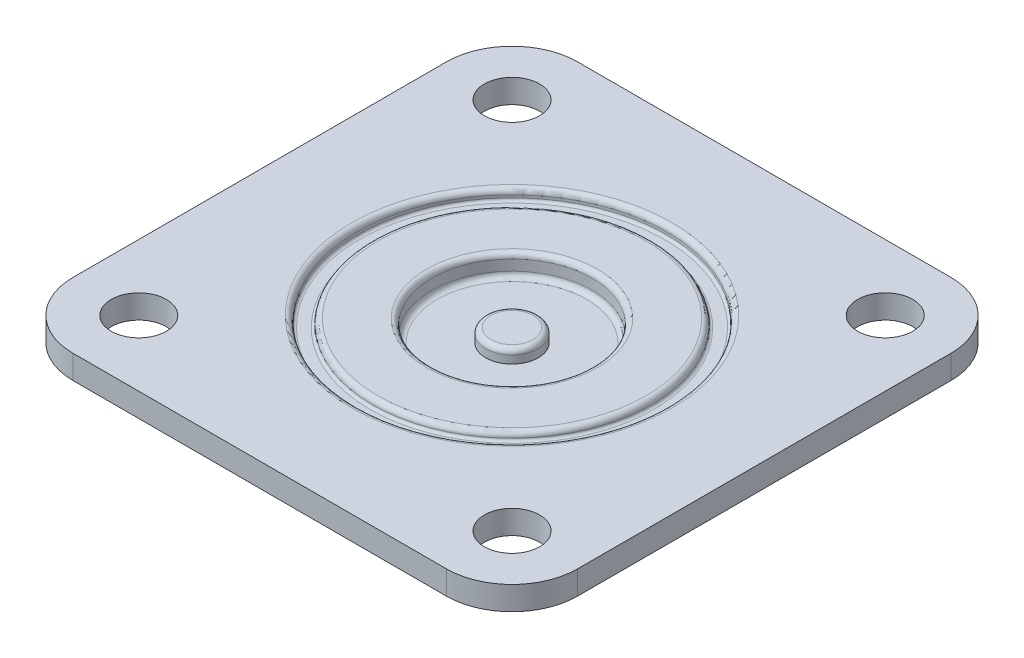
SolidWorks part; units mm, degrees
ref_plane "前视基准面" through (0, 0, 0) normal (0, 0, 1) x (1, 0, 0)
ref_plane "上视基准面" through (0, 0, 0) normal (0, 1, 0) x (1, 0, 0)
ref_plane "右视基准面" through (0, 0, 0) normal (1, 0, 0) x (0, 0, -1)
ref_plane "基准面4" through (0, 0, 0) normal (0, 1, 0) x (1, 0, 0)
sketch "草图1" plane through (0, 0, 0) normal (0, 1, 0) x (1, 0, 0)
  line L0 (-35.5, -48) -> (35.5, -48)
  line L1 (48, -35.5) -> (48, 35.5)
  line L2 (35.5, 48) -> (-35.5, 48)
  line L3 (-48, 35.5) -> (-48, -35.5)
  arc A0 (-48, -35.5) -> (-35.5, -48) centre (-35.5, -35.5) ccw
  arc A1 (35.5, -48) -> (48, -35.5) centre (35.5, -35.5) ccw
  arc A2 (48, 35.5) -> (35.5, 48) centre (35.5, 35.5) ccw
  arc A3 (-35.5, 48) -> (-48, 35.5) centre (-35.5, 35.5) ccw
  circle A4 centre (35.5, -35.5) radius 5.25
  circle A5 centre (35.5, 35.5) radius 5.25
  circle A6 centre (-35.5, -35.5) radius 5.25
  circle A7 centre (-35.5, 35.5) radius 5.25
extrude "凸台-拉伸1" add sketch "草图1" against normal blind 4.5
ref_plane "基准面5" through (0, 0, 0) normal (0, 0, 1) x (1, 0, 0)
sketch "草图2" plane through (0, 0, 0) normal (0, 0, 1) x (1, 0, 0)
  line L0 (0, -4.5) -> (35.5, -4.5)
  line L1 (35.5, -4.5) -> (27.9989, -15.9639)
  line L2 (24.2334, -18) -> (0, -18)
  line L3 (0, -18) -> (0, -4.5)
  line L4 (0, -18) -> (0, -4.5) construction
  arc A0 (27.9989, -15.9639) -> (24.2334, -18) centre (24.2334, -13.5) cw
revolve "旋转1" add sketch "草图2" angle 360 about L4
ref_plane "基准面6" through (0, 0, 0) normal (0, 0, 1) x (1, 0, 0)
sketch "草图3" plane through (0, 0, 0) normal (0, 0, 1) x (1, 0, 0)
  line L0 (0, 0) -> (30.5, 0)
  line L1 (29.5, -1) -> (29.5, -1.5)
  line L2 (29, -2) -> (27, -2)
  line L3 (25.5, -0.5) -> (16.25, -0.5)
  line L4 (15.25, -1.5) -> (15.25, -3.5)
  line L5 (14.25, -4.5) -> (5, -4.5)
  line L6 (5, -4.5) -> (5, -3)
  line L7 (4, -2) -> (0, -2)
  line L8 (0, -2) -> (0, 0)
  line L9 (0, -2) -> (0, 0) construction
  arc A0 (30.5, 0) -> (29.5, -1) centre (30.5, -1) ccw
  arc A1 (29.5, -1.5) -> (29, -2) centre (29, -1.5) cw
  arc A2 (27, -2) -> (26.5, -1.5) centre (27, -1.5) cw
  arc A3 (26.5, -1.5) -> (25.5, -0.5) centre (25.5, -1.5) ccw
  arc A4 (16.25, -0.5) -> (15.25, -1.5) centre (16.25, -1.5) ccw
  arc A5 (15.25, -3.5) -> (14.25, -4.5) centre (14.25, -3.5) cw
  arc A6 (5, -3) -> (4, -2) centre (4, -3) ccw
revolve "切除-旋转1" cut sketch "草图3" angle 360 about L9
